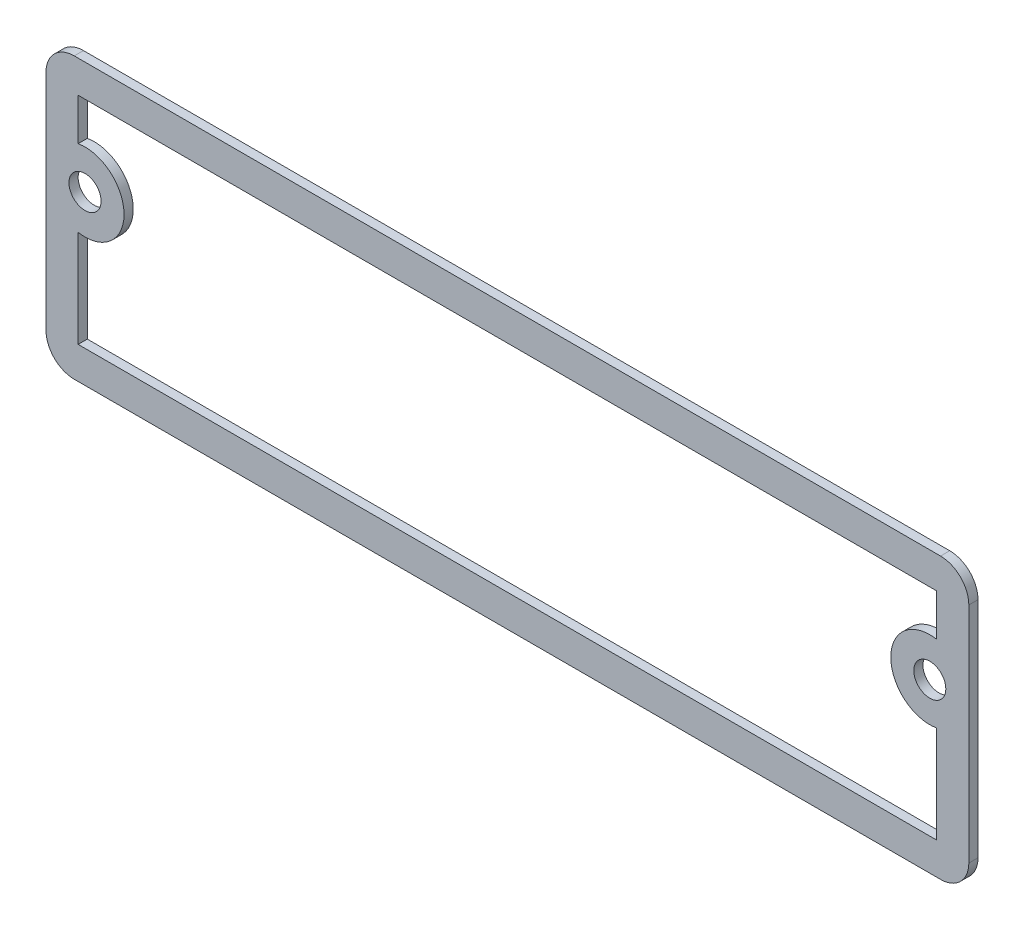
SolidWorks part; units mm, degrees
ref_plane "Front" through (0, 0, 0) normal (0, 0, 1) x (1, 0, 0)
ref_plane "Top" through (0, 0, 0) normal (0, 1, 0) x (1, 0, 0)
ref_plane "Right" through (0, 0, 0) normal (1, 0, 0) x (0, 0, -1)
sketch "Sketch2" plane through (0, 0, 0) normal (0, 0, 1) x (1, 0, 0)
  line L8 (0, 3) -> (0, 27)
  line L9 (-3, 30) -> (-97, 30)
  line L10 (-100, 27) -> (-100, 3)
  line L11 (-97, 0) -> (-3, 0)
  line L14 (-97, 27) -> (-3, 27)
  line L15 (-97, 27) -> (-97, 21.873)
  line L16 (-3, 27) -> (-3, 21.873)
  line L17 (-3, 14.127) -> (-3, 3)
  line L18 (-97, 3) -> (-3, 3)
  line L19 (-97, 14.127) -> (-97, 3)
  circle A1 centre (-96, 18) radius 1.75
  arc A8 (-3, 0) -> (0, 3) centre (-3, 3) ccw
  arc A9 (0, 27) -> (-3, 30) centre (-3, 27) ccw
  arc A10 (-97, 30) -> (-100, 27) centre (-97, 27) ccw
  arc A11 (-100, 3) -> (-97, 0) centre (-97, 3) ccw
  arc A13 (-3, 21.873) -> (-3, 14.127) centre (-4, 18) ccw
  circle A14 centre (-4, 18) radius 1.75
  arc A15 (-97, 14.127) -> (-97, 21.873) centre (-96, 18) ccw
extrude "Boss-Extrude1" add sketch "Sketch2" along normal blind 1
sketch "Sketch4" plane through (0, 0, 1) normal (0, 0, 1) x (1, 0, 0)
  line L0 (-3, 30) -> (-97, 30) construction
  line L1 (-97.1715, 30.25) -> (-2.8285, 30.25)
  line L2 (-100.25, 27.1715) -> (-100.25, 2.8285)
  line L3 (-97.1715, -0.25) -> (-2.8285, -0.25)
  line L4 (0.25, 27.1715) -> (0.25, 2.8285)
  line L5 (-97, 0) -> (-3, 0) construction
  line L6 (-100, 27) -> (-100, 3) construction
  line L7 (0, 3) -> (0, 27) construction
  line L8 (-3, 27) -> (-97, 27) construction
  line L9 (-96.75, 26.75) -> (-3.25, 26.75)
  line L10 (-96.75, 26.75) -> (-96.75, 3.25) construction
  line L11 (-96.75, 3.25) -> (-3.25, 3.25)
  line L12 (-3.25, 26.75) -> (-3.25, 3.25) construction
  line L13 (-97, 27) -> (-97, 21.873) construction
  line L14 (-97, 3) -> (-3, 3) construction
  line L15 (-3, 3) -> (-3, 14.127) construction
  line L16 (-100.25, 18) -> (0.25, 18) construction
  line L17 (-96.75, 26.75) -> (-96.75, 22.1833)
  line L18 (-96.75, 13.8167) -> (-96.75, 3.25)
  line L19 (-3.25, 26.75) -> (-3.25, 22.1833)
  line L20 (-3.25, 13.8167) -> (-3.25, 3.25)
  arc A0 (-2.8285, 30.25) -> (0.25, 27.1715) centre (-2.8285, 27.1715) cw
  arc A1 (-2.8285, -0.25) -> (0.25, 2.8285) centre (-2.8285, 2.8285) ccw
  arc A2 (-97.1715, -0.25) -> (-100.25, 2.8285) centre (-97.1715, 2.8285) cw
  arc A3 (-100.25, 27.1715) -> (-97.1715, 30.25) centre (-97.1715, 27.1715) cw
  arc A4 (-3.25, 22.1833) -> (-3.25, 13.8167) centre (-4, 18) ccw
  arc A5 (-96.75, 22.1833) -> (-96.75, 13.8167) centre (-96, 18) cw
  circle A6 centre (-96, 18) radius 1.75
  circle A7 centre (-4, 18) radius 1.7441
  point P10 (0, 15)
  point P19 (-97, 24.4365)
  point P36 (-4, 18)
  dimension "D9" = 3.0785
  dimension "D10" = 4.25
  dimension "D11" = 4.25
  dimension "D1" = 0.25
  dimension "D2" = 0.25
  dimension "D3" = 0.25
  dimension "D4" = 0.25
  dimension "D5" = 0.25
  dimension "D6" = 0.25
  dimension "D7" = 0.25
  dimension "D8" = 0.25
extrude "Boss-Extrude3" add sketch "Sketch4" against normal up to surface (1 mm away) up to face at (-50, 16.5, 0)
equation "\"Seal\"=0.25"
equation "\"D4@Sketch4\"=\"Seal\""
equation "\"D1@Sketch4\"=\"Seal\""
equation "\"D3@Sketch4\"=\"Seal\""
equation "\"D2@Sketch4\"=\"Seal\""
equation "\"D5@Sketch4\"=\"Seal\""
equation "\"D7@Sketch4\"=\"Seal\""
equation "\"D6@Sketch4\"=\"Seal\""
equation "\"D8@Sketch4\"=\"Seal\""
equation "\"HoleSeal\"=4.25"
equation "\"D10@Sketch4\"=\"HoleSeal\""
equation "\"D11@Sketch4\"=\"HoleSeal\""
